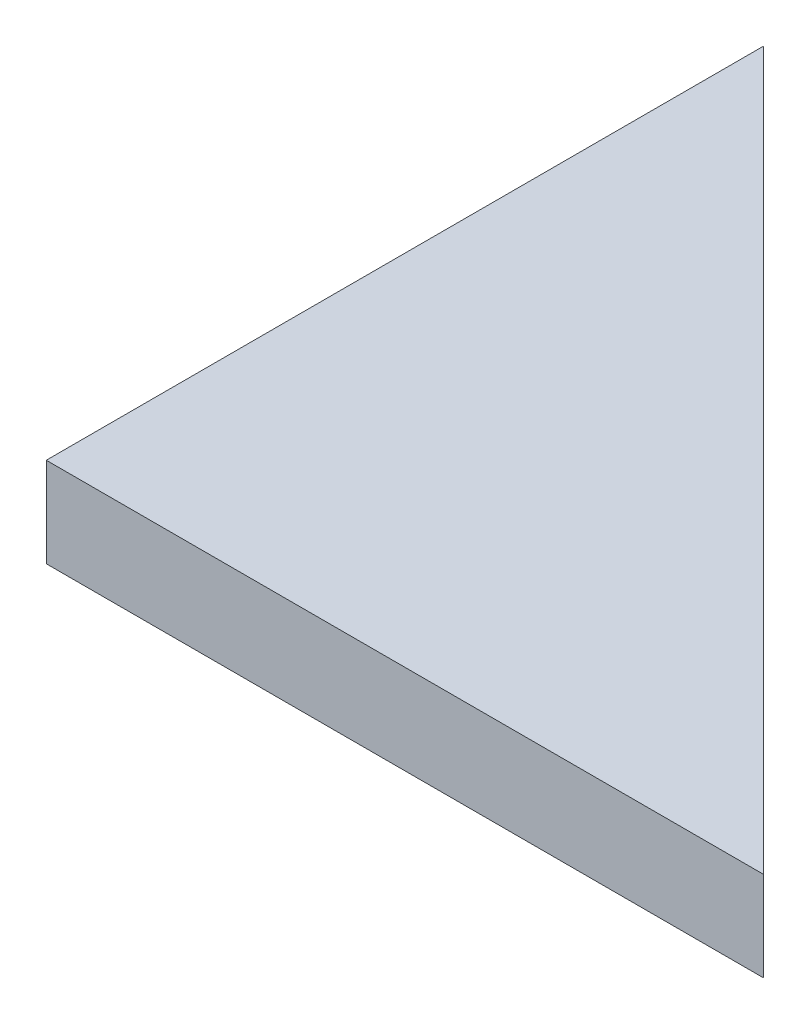
SolidWorks part; units mm, degrees
ref_plane "Front Plane" through (0, 0, 0) normal (0, 0, 1) x (1, 0, 0)
ref_plane "Top Plane" through (0, 0, 0) normal (0, 1, 0) x (1, 0, 0)
ref_plane "Right Plane" through (0, 0, 0) normal (1, 0, 0) x (0, 0, -1)
sketch "Sketch1" plane through (0, 0, 0) normal (0, 1, 0) x (1, 0, 0)
  line L0 (0, 0) -> (0, 0.8)
  line L1 (0, 0.8) -> (0.8, 0)
  line L2 (0.8, 0) -> (0, 0)
  dimension "D1" = 0.8
  dimension "D2" = 0.8
extrude "Boss-Extrude1" add sketch "Sketch1" along normal blind 0.1
